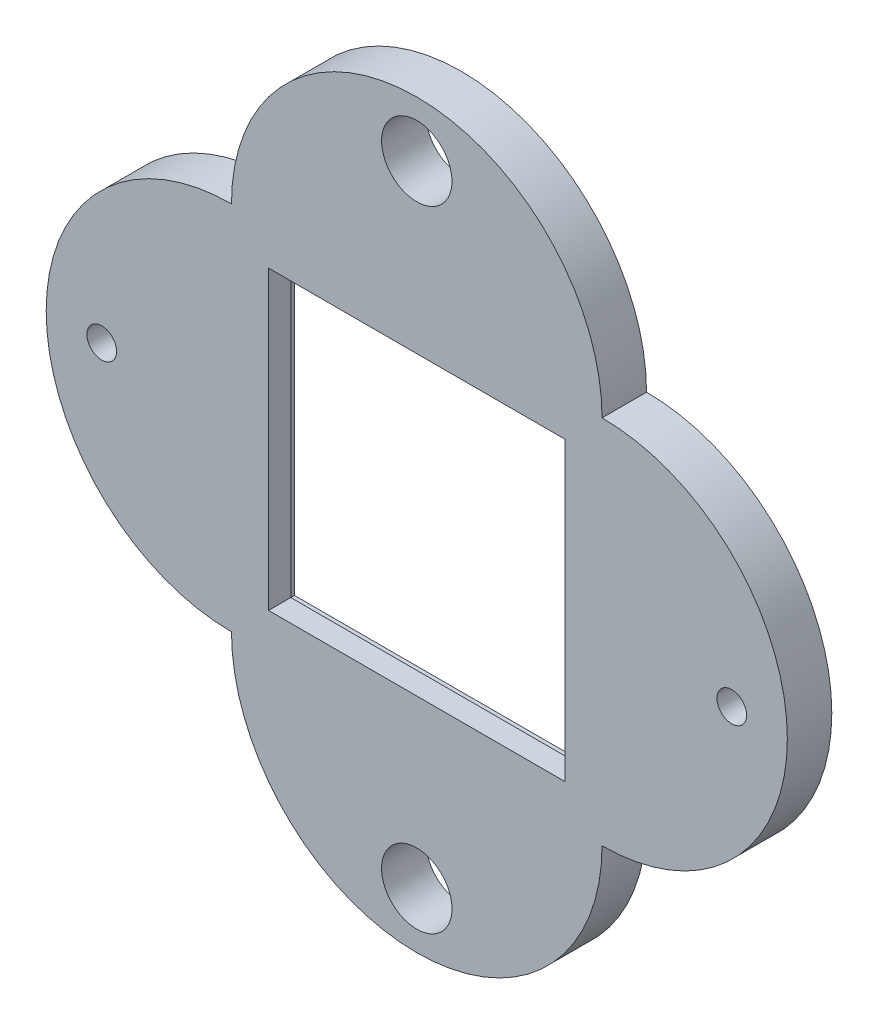
SolidWorks part; units mm, degrees
ref_plane "Ön Düzlem" through (0, 0, 0) normal (0, 0, 1) x (1, 0, 0)
ref_plane "Üst Düzlem" through (0, 0, 0) normal (0, 1, 0) x (1, 0, 0)
ref_plane "Sağ Düzlem" through (0, 0, 0) normal (1, 0, 0) x (0, 0, -1)
sketch "Çizim1" plane through (0, 0, 0) normal (0, 0, 1) x (1, 0, 0)
  line L0 (-4.0541, 43.048) -> (-4.0541, -46.952)
  line L1 (-49.0541, 43.048) -> (40.9459, 43.048)
  line L2 (-49.0541, 43.048) -> (-49.0541, -46.952)
  line L3 (-49.0541, -46.952) -> (40.9459, -46.952)
  line L4 (40.9459, 43.048) -> (40.9459, -46.952)
  line L5 (-49.0541, -1.952) -> (40.9459, -1.952)
  arc A0 (45.9459, 48.048) -> (-54.0541, 48.048) centre (-4.0541, 48.048) ccw
  arc A1 (45.9459, -51.952) -> (45.9459, 48.048) centre (45.9459, -1.952) ccw
  arc A2 (-54.0541, -51.952) -> (45.9459, -51.952) centre (-4.0541, -51.952) ccw
  arc A3 (-54.0541, 48.048) -> (-54.0541, -51.952) centre (-54.0541, -1.952) ccw
  circle A4 centre (-4.0541, 83.048) radius 5.8468
  circle A5 centre (-4.0541, 83.048) radius 9.5
  circle A6 centre (-89.0541, -1.952) radius 4
  circle A7 centre (-4.0541, -86.952) radius 9.5
  circle A8 centre (80.9459, -1.952) radius 4
  dimension "D8" = 35
  dimension "D9" = 19
  dimension "D10" = 35
  dimension "D11" = 8
  dimension "D1" = 100
  dimension "D2" = 100
  dimension "D3" = 90
  dimension "D4" = 90
  dimension "D5" = 5
  dimension "D6" = 5
  dimension "D7" = 5
extrude "Yükseklik-Ekstrüzyon1" add sketch "Çizim1" along normal blind 12 contours A0 A3 A2 A1 A7 A6 A5 L1 L4 L3 L2 A8
sketch "Çizim2" plane through (0, 0, 12) normal (0, 0, 1) x (1, 0, 0)
  line L1 (-49.0541, 43.048) -> (40.9459, 43.048)
  line L2 (-49.0541, 43.048) -> (-49.0541, -46.952)
  line L3 (-49.0541, -46.952) -> (40.9459, -46.952)
  line L4 (40.9459, 43.048) -> (40.9459, -46.952)
  line L5 (-44.0541, 38.048) -> (35.9459, 38.048)
  line L6 (-44.0541, 38.048) -> (-44.0541, -41.952)
  line L7 (-44.0541, -41.952) -> (35.9459, -41.952)
  line L8 (35.9459, 38.048) -> (35.9459, -41.952)
  dimension "D1" = 80
  dimension "D2" = 80
  dimension "D3" = 5
  dimension "D4" = 5
extrude "Yükseklik-Ekstrüzyon2" add sketch "Çizim2" against normal blind 6
